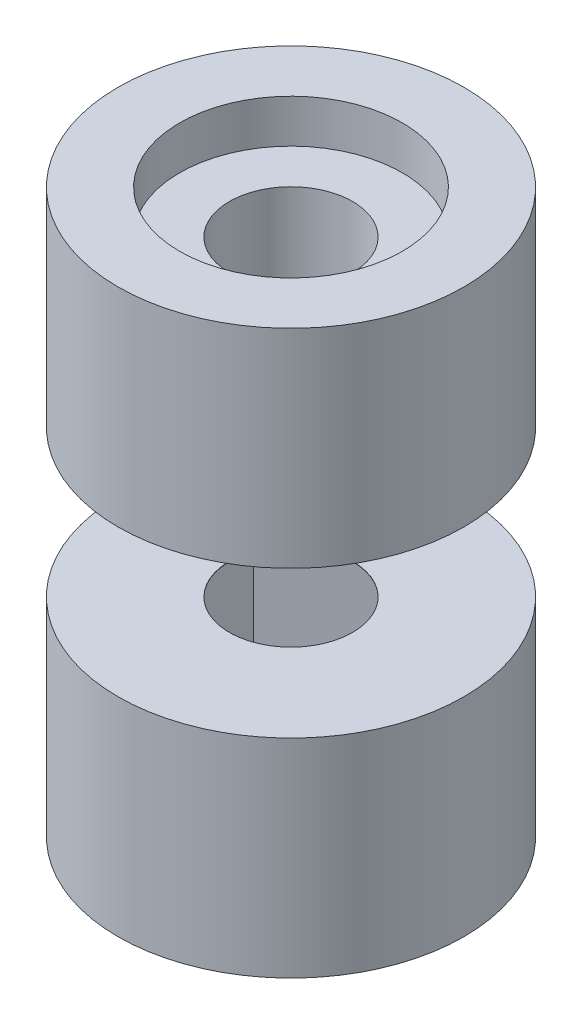
SolidWorks part; units mm, degrees
ref_plane "Front Plane" through (0, 0, 0) normal (0, 0, 1) x (1, 0, 0)
ref_plane "Top Plane" through (0, 0, 0) normal (0, 1, 0) x (1, 0, 0)
ref_plane "Right Plane" through (0, 0, 0) normal (1, 0, 0) x (0, 0, -1)
sketch "Sketch1" plane through (0, 0, 0) normal (0, 1, 0) x (1, 0, 0)
  circle A0 centre (0, 0) radius 8
extrude "Boss-Extrude1" add sketch "Sketch1" along normal blind 26.03
sketch "Sketch2" plane through (0, 0, 0) normal (0, 0, 1) x (1, 0, 0)
  line L0 (-10.2, 9.615) -> (10.2, 9.615)
  line L1 (10.2, 9.615) -> (10.2, 16.415)
  line L2 (10.2, 16.415) -> (-10.2, 16.415)
  line L3 (-10.2, 16.415) -> (-10.2, 9.615)
extrude "Cut-Extrude1" cut sketch "Sketch2" against normal through all and the other way through all
sketch "Sketch3" plane through (0, 0, 0) normal (0, 1, 0) x (1, 0, 0)
  circle A0 centre (0, 0) radius 2.85
extrude "Cut-Extrude2" cut sketch "Sketch3" along normal blind 26.03
ref_plane "Plane1" through (0, 26.03, 0) normal (0, 1, 0) x (1, 0, 0)
sketch "Sketch4" plane through (0, 26.03, 0) normal (0, 1, 0) x (1, 0, 0)
  circle A0 centre (0, 0) radius 5.15
extrude "Cut-Extrude3" cut sketch "Sketch4" against normal blind 2
sketch "Sketch5" plane through (0, 0, 0) normal (0, 1, 0) x (1, 0, 0)
  line L0 (4.1, -2.3671) -> (0, -4.7343)
  line L1 (0, -4.7343) -> (-4.1, -2.3671)
  line L2 (-4.1, -2.3671) -> (-4.1, 2.3671)
  line L3 (-4.1, 2.3671) -> (0, 4.7343)
  line L4 (0, 4.7343) -> (4.1, 2.3671)
  line L5 (4.1, 2.3671) -> (4.1, -2.3671)
extrude "Cut-Extrude4" cut sketch "Sketch5" along normal blind 9.6
